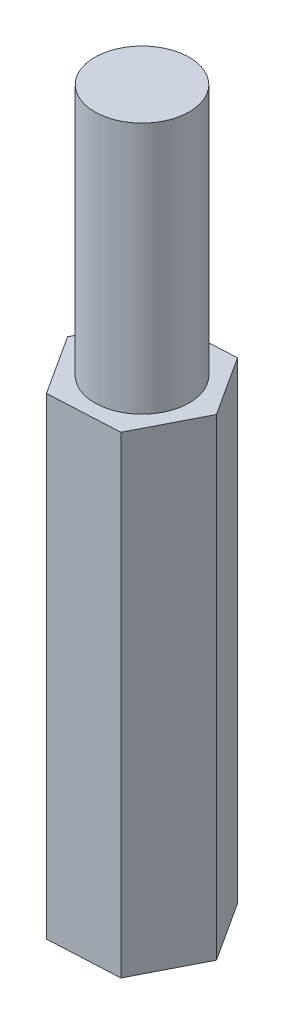
SolidWorks part; units mm, degrees
ref_plane "前视基准面" through (0, 0, 0) normal (0, 0, 1) x (1, 0, 0)
ref_plane "上视基准面" through (0, 0, 0) normal (0, 1, 0) x (1, 0, 0)
ref_plane "右视基准面" through (0, 0, 0) normal (1, 0, 0) x (0, 0, -1)
other "Configuration Table"
sketch "草图1" plane through (0, 0, 0) normal (0, 1, 0) x (1, 0, 0)
  line L1 (1.2233, -1.8918) -> (2.25, 0.1135)
  line L2 (2.25, 0.1135) -> (1.0267, 2.0053)
  line L3 (1.0267, 2.0053) -> (-1.2233, 1.8918)
  line L4 (-1.2233, 1.8918) -> (-2.25, -0.1135)
  line L5 (-2.25, -0.1135) -> (-1.0267, -2.0053)
  line L6 (-1.0267, -2.0053) -> (1.2233, -1.8918)
  circle A0 centre (0, 0) radius 1.951 construction
  dimension "D1" = 4.5
extrude "凸台-拉伸1" add sketch "草图1" along normal blind 15
sketch "草图2" plane through (0, 15, 0) normal (0, 1, 0) x (1, 0, 0)
  circle A0 centre (0, 0) radius 1.5
  dimension "D1" = 3
extrude "凸台-拉伸2" add sketch "草图2" along normal blind 8
